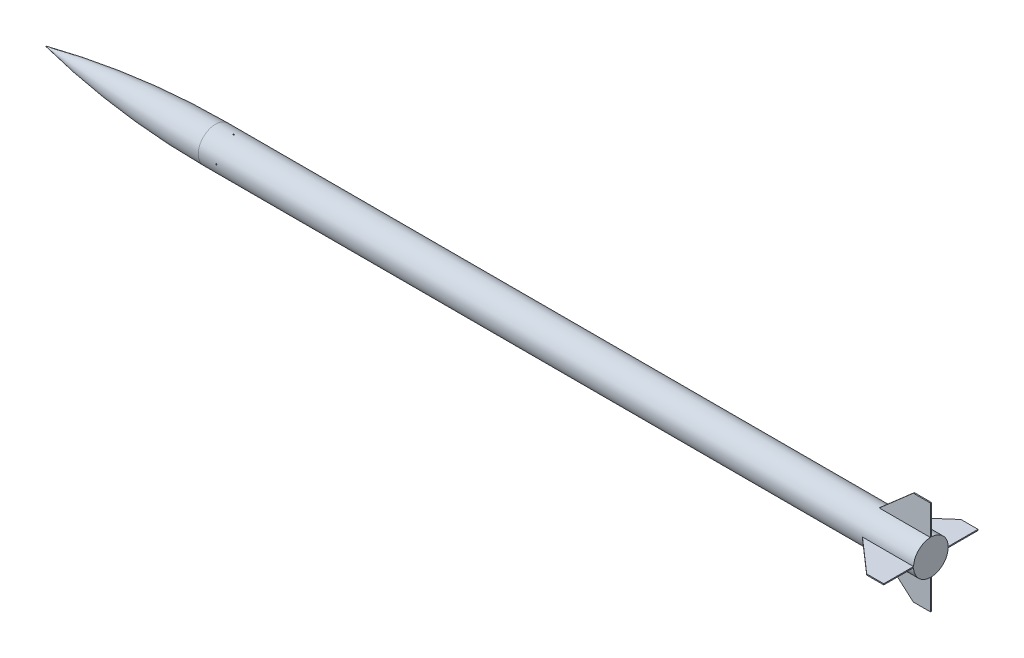
SolidWorks part; units mm, degrees
ref_plane "Front Plane" through (0, 0, 0) normal (0, 0, 1) x (1, 0, 0)
ref_plane "Top Plane" through (0, 0, 0) normal (0, 1, 0) x (1, 0, 0)
ref_plane "Right Plane" through (0, 0, 0) normal (1, 0, 0) x (0, 0, -1)
sketch "Sketch1" plane through (0, 0, 0) normal (0, 0, 1) x (1, 0, 0)
  line L0 (2133.6, 0) -> (-505.4713, 0)
  line L1 (2133.6, 0) -> (2133.6, -51.6636)
  line L8 (0, -51.6636) -> (2133.6, -51.6636)
  arc A1 (0, -51.6636) -> (-504.9634, -0.6222) centre (0, 2471.71) cw
  arc A2 (-504.9634, -0.6222) -> (-505.4713, 0) centre (-504.8363, 0) cw
  dimension "D3" = 0.635
revolve "Revolve10" add sketch "Sketch1" angle 360 about L0
sketch "Sketch2" plane through (0, 0, 0) normal (0, 0, 1) x (1, 0, 0)
  line L1 (1981.2, 51.6636) -> (2133.6, 51.6636)
  line L3 (2133.6, 51.6636) -> (2133.6, 140.5636)
  line L4 (2133.6, 51.6636) -> (0, 51.6636) construction
  line L5 (2082.8, 140.5636) -> (1981.2, 51.6636)
  line L6 (2133.6, 140.5636) -> (2082.8, 140.5636)
  dimension "D1" = 152.4
extrude "Boss-Extrude2" add sketch "Sketch2" along normal mid plane 3.175 separate body
pattern_circular "CirPattern4" count 4 over 360 about axis through (0, 0, 0) along (1, 0, 0) of bodies 103
sketch "Sketch3" plane through (0, 0, 0) normal (0, 0, 1) x (1, 0, 0)
  line L0 (-504.9634, 0.6222) -> (53.8366, 0.6222) construction
  circle A0 centre (53.8366, 0.6222) radius 1.5977
  dimension "D2" = 3.1953
  dimension "D1" = 558.8
extrude "Cut-Extrude1" cut sketch "Sketch3" against normal mid plane 152.4
sketch "Sketch4" plane through (0, 0, 0) normal (0, 1, 0) x (1, 0, 0)
  line L0 (-505.4713, 0) -> (53.8367, 0) construction
  arc A0 (-504.9634, 0.6222) -> (-504.9634, -0.6222) centre (-504.8363, 0) ccw construction
  circle A1 centre (53.8367, 0) radius 1.5977
  dimension "D2" = 3.1953
  dimension "D1" = 559.308
extrude "Cut-Extrude2" cut sketch "Sketch4" against normal mid plane 152.4
